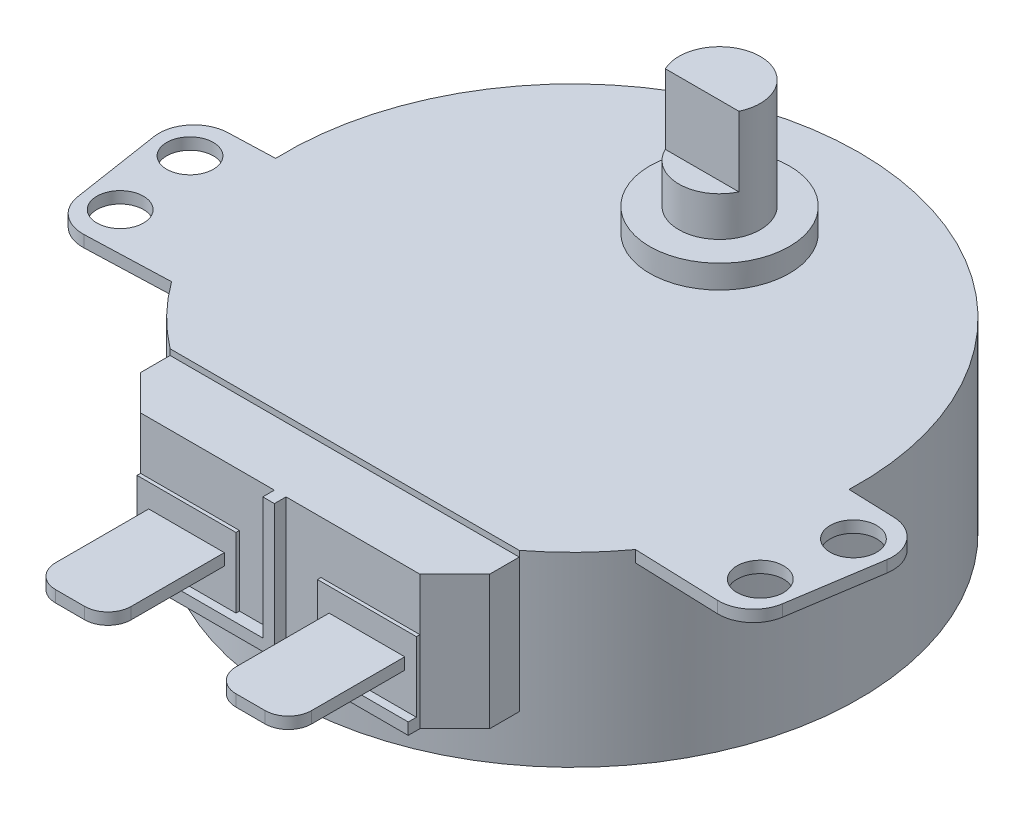
SolidWorks part; units mm, degrees
ref_plane "Frontal" through (0, 0, 0) normal (0, 0, 1) x (1, 0, 0)
ref_plane "Superior" through (0, 0, 0) normal (0, 1, 0) x (1, 0, 0)
ref_plane "Lateral" through (0, 0, 0) normal (1, 0, 0) x (0, 0, -1)
sketch "Esboço1" plane through (0, 0, 0) normal (0, 0, 1) x (1, 0, 0)
  line L0 (0, 0) -> (0, 52.8402) construction
  line L1 (0, 0) -> (-24.65, 0)
  line L2 (-24.65, 0) -> (-24.65, 16)
  line L3 (-24.65, 16) -> (0, 16)
  line L4 (0, 16) -> (0, 0)
  dimension "D1" = 16
  dimension "D2" = 49.3
revolve "Revolução1" add sketch "Esboço1" angle 360 about L0
sketch "Esboço2" plane through (0, 0, 0) normal (0, 0, 1) x (1, 0, 0)
  line L0 (24.65, 16) -> (-24.65, 16) construction
  line L1 (-15, 16) -> (15, 16)
  line L2 (-15, 16) -> (-15, 4)
  line L3 (-15, 4) -> (15, 4)
  line L4 (15, 16) -> (15, 4)
  line L5 (0, 0) -> (0, 16) construction
  line L6 (-24.65, 0) -> (24.65, 0) construction
  dimension "D1" = 12
  dimension "D2" = 30
extrude "Extrusão1" add sketch "Esboço2" along normal blind 25.1
chamfer "Chanfro1" distance 3 angle 45 2 edges at (15, 10, 25.1) (-15, 10, 25.1)
sketch "Esboço4" plane through (0, 0, 25.1) normal (0, 0, 1) x (1, 0, 0)
  line L0 (-12, 5) -> (-0.5, 5)
  line L1 (-12, 16) -> (-12, 4) construction
  line L2 (-0.5, 5) -> (-0.5, 16)
  line L3 (12, 16) -> (-12, 16) construction
  line L4 (0, 4) -> (0, 16) construction
  line L5 (-12, 4) -> (12, 4) construction
  line L6 (-15, 4) -> (15, 4) construction
  line L7 (-12, 5) -> (-12, 4)
  line L8 (-12, 4) -> (12, 4)
  line L9 (-0.5, 16) -> (0.5, 16)
  line L10 (12, 5) -> (12, 4)
  line L11 (0.5, 5) -> (0.5, 16)
  line L12 (12, 5) -> (0.5, 5)
  dimension "D1" = 1
  dimension "D2" = 1
extrude "Extrusão2" add sketch "Esboço4" along normal blind 1
sketch "Esboço5" plane through (0, 0, 25.1) normal (0, 0, 1) x (1, 0, 0)
  line L0 (-0.5, 5) -> (-12, 5) construction
  line L1 (-12, 5) -> (-3.5, 5)
  line L2 (-12, 5) -> (-12, 11)
  line L3 (-12, 11) -> (-3.5, 11)
  line L4 (-3.5, 5) -> (-3.5, 11)
  line L5 (0, 16) -> (0, 4) construction
  line L6 (0.5, 16) -> (-0.5, 16) construction
  line L7 (-12, 4) -> (12, 4) construction
  line L8 (-0.5, 16) -> (-0.5, 5) construction
  line L9 (3.5, 5) -> (3.5, 11)
  line L10 (12, 11) -> (3.5, 11)
  line L11 (12, 5) -> (12, 11)
  line L12 (12, 5) -> (3.5, 5)
  dimension "D1" = 8.5
  dimension "D2" = 3
  dimension "D3" = 7
extrude "Extrusão3" add sketch "Esboço5" along normal blind 0.3
sketch "Esboço6" plane through (0, 0, 25.4) normal (0, 0, 1) x (1, 0, 0)
  line L0 (0, 16) -> (0, 4) construction
  line L1 (-11, 9) -> (-4.5, 9)
  line L2 (-11, 9) -> (-11, 8)
  line L3 (-11, 8) -> (-4.5, 8)
  line L4 (-4.5, 9) -> (-4.5, 8)
  line L5 (0.5, 16) -> (-0.5, 16) construction
  line L6 (-15, 4) -> (15, 4) construction
  line L7 (-12, 4) -> (12, 4) construction
  line L8 (-7.75, 11) -> (-7.75, 9) construction
  line L9 (-3.5, 11) -> (-12, 11) construction
  line L10 (7.75, 11) -> (7.75, 9) construction
  line L11 (4.5, 9) -> (4.5, 8)
  line L12 (11, 8) -> (4.5, 8)
  line L13 (11, 9) -> (11, 8)
  line L14 (11, 9) -> (4.5, 9)
  dimension "D1" = 6.5
  dimension "D2" = 1
  dimension "D3" = 4
extrude "Extrusão4" add sketch "Esboço6" along normal blind 10
sketch "Esboço7" plane through (0, 16, 0) normal (0, 1, 0) x (1, 0, 0)
  line L0 (0, 0) -> (-31.7458, -4.4616) construction
  line L1 (0, 0) -> (0, -26.1) construction
  line L2 (0.5, -26.1) -> (-0.5, -26.1) construction
  line L3 (0, 0) -> (-32.5, 0) construction
  line L4 (-24.635, -0.8603) -> (-32, -1.1175)
  line L5 (0.4816, -13.7916) -> (0, -13.8084)
  line L6 (0.4816, -13.7916) -> (-31.5184, -14.9091) construction
  line L7 (-19.931, -14.5044) -> (-29.8756, -14.8517)
  line L8 (0, 0) -> (-32, -1.1175) construction
  line L9 (-24.635, -0.8603) -> (0, 0) construction
  line L10 (-32, -1.1175) -> (-29.8756, -14.8517)
  line L11 (-28.5, -4.35) -> (-31.5, -4.35) construction
  line L12 (28.5, -4.35) -> (31.5, -4.35) construction
  line L13 (32, -1.1175) -> (29.8756, -14.8517)
  line L14 (19.931, -14.5044) -> (29.8756, -14.8517)
  line L15 (24.635, -0.8603) -> (32, -1.1175)
  circle A0 centre (28.5, -4.35) radius 2
  arc A1 (-24.635, -0.8603) -> (-19.931, -14.5044) centre (0, 0) ccw
  arc A2 (15, -19.5607) -> (-15, -19.5607) centre (0, 0) ccw construction
  circle A3 centre (-27.5, -11.35) radius 2
  circle A4 centre (-28.5, -4.35) radius 2
  circle A5 centre (27.5, -11.35) radius 2
  arc A6 (24.635, -0.8603) -> (19.931, -14.5044) centre (0, 0) cw
  arc M4 (15, -19.5607) -> (-15, -19.5607) centre (0, 0) ccw
  dimension "D1" = 64
  dimension "D3" = 4
  dimension "D7" = 29
  dimension "D2" = 8
  dimension "D4" = 55
  dimension "D5" = 57
  dimension "D6" = 7
  dimension "D9" = 2
  dimension "D10" = 3
  dimension "D8" = 13.8
extrude "Extrusão5" add sketch "Esboço7" against normal blind 1 contours L4 L10 L7 A4 A3 M4 | L15 L14 L13 A0 A5 M4
fillet "Filete1" radius 3 4 edges at (32, 15.5, 1.1175) (29.8756, 15.5, 14.8517) (-32, 15.5, 1.1175) (-29.8756, 15.5, 14.8517)
sketch "Esboço8" plane through (0, 16, 0) normal (0, 1, 0) x (1, 0, 0)
  circle A0 centre (0, 12.65) radius 6
  arc A1 (24.635, -0.8603) -> (-24.635, -0.8603) centre (0, 0) ccw construction
  dimension "D1" = 12
  dimension "D2" = 18
extrude "Extrusão6" add sketch "Esboço8" along normal blind 2
sketch "Esboço9" plane through (0, 18, 0) normal (0, 1, 0) x (1, 0, 0)
  circle A0 centre (0, 12.65) radius 3.5
  dimension "D1" = 7
extrude "Extrusão7" add sketch "Esboço9" along normal blind 9.4
sketch "Esboço10" plane through (0, 27.4, 0) normal (0, 1, 0) x (1, 0, 0)
  line L1 (-3.1623, 11.15) -> (3.1623, 11.15)
  line L2 (-3.1623, 11.15) -> (-3.1623, 7.551)
  line L3 (-3.1623, 7.551) -> (3.1623, 7.551)
  line L4 (3.1623, 11.15) -> (3.1623, 7.551)
  circle A0 centre (0, 12.65) radius 3.5 construction
  circle A1 centre (0, 12.65) radius 6 construction
  circle A2 centre (0, 12.65) radius 3.5 construction
  dimension "D1" = 5
extrude "Extrusão8" cut sketch "Esboço10" against normal blind 6
sketch "Esboço11" plane through (0, 16, 0) normal (0, 1, 0) x (1, 0, 0)
  line L0 (15, -22.1) -> (15, -19.5607) construction
  line L1 (-15, -19.5607) -> (15, -19.5607)
  line L2 (-15, -19.5607) -> (-15, -28.6691)
  line L3 (-15, -28.6691) -> (15, -28.6691)
  line L4 (15, -19.5607) -> (15, -28.6691)
extrude "Extrusão9" cut sketch "Esboço11" against normal blind 0.5
fillet "Filete2" radius 2 4 edges at (4.5, 8.5, 35.4) (11, 8.5, 35.4) (-11, 8.5, 35.4) (-4.5, 8.5, 35.4)
sketch "Esboço12" plane through (0, 0, 0) normal (1, 0, 0) x (0, 0, -1)
  line L0 (12.65, 18) -> (12.65, 30.3452) construction
  line L1 (18.65, 18) -> (6.65, 18) construction
ref_plane "Plano1" through (-6.325, 0, -6.325) normal (0.7071, 0, 0.7071) x (0.7071, 0, -0.7071)
